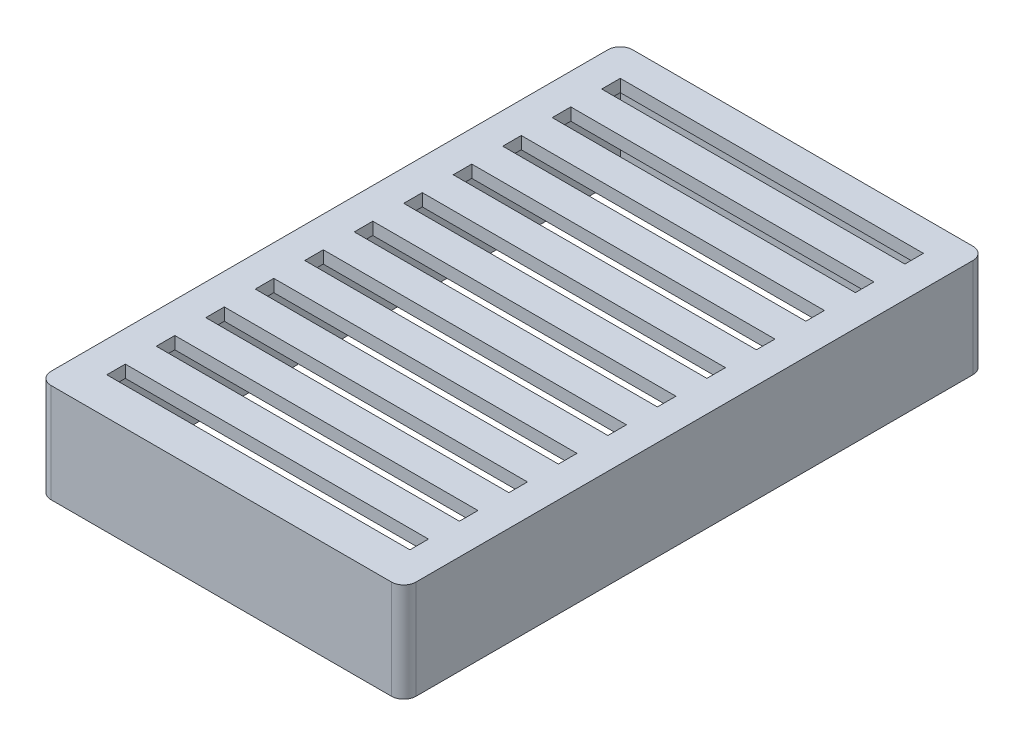
SolidWorks part; units mm, degrees
ref_plane "Front Plane" through (0, 0, 0) normal (0, 0, 1) x (1, 0, 0)
ref_plane "Top Plane" through (0, 0, 0) normal (0, 1, 0) x (1, 0, 0)
ref_plane "Right Plane" through (0, 0, 0) normal (1, 0, 0) x (0, 0, -1)
sketch "Sketch1" plane through (0, 15, 0) normal (0, 1, 0) x (1, 0, 0)
  line L27 (26.5, 24) -> (-26.5, 24)
  line L28 (-26.5, 24) -> (-26.5, -64)
  line L29 (-26.5, -64) -> (26.5, -64)
  line L30 (26.5, -64) -> (26.5, 24)
  line L31 (-27.5, -67) -> (27.5, -67)
  line L32 (-29.5, 25) -> (-29.5, -65)
  line L33 (27.5, 27) -> (-27.5, 27)
  line L34 (29.5, -65) -> (29.5, 25)
  line L35 (-27.5, -67) -> (27.5, -67)
  line L36 (-29.5, 25) -> (-29.5, -65)
  line L37 (27.5, 27) -> (-27.5, 27)
  line L38 (29.5, -65) -> (29.5, 25)
  line L39 (0, 24) -> (0, -64) construction
  line L41 (-11, 24) -> (-9, 24)
  line L44 (-11, -64) -> (-9, -64)
  line L49 (0, 21.1819) -> (0, 0) construction
  line L51 (-26.5, 22) -> (-26.5, 20)
  line L53 (0, 22) -> (0, 20)
  arc A24 (-26.5, 24) -> (-26.5, 24) centre (-26.5, 24) ccw
  arc A25 (-26.5, -64) -> (-26.5, -64) centre (-26.5, -64) ccw
  arc A26 (26.5, -64) -> (26.5, -64) centre (26.5, -64) ccw
  arc A27 (26.5, 24) -> (26.5, 24) centre (26.5, 24) ccw
  arc A28 (27.5, -67) -> (29.5, -65) centre (27.5, -65) ccw
  arc A29 (-29.5, -65) -> (-27.5, -67) centre (-27.5, -65) ccw
  arc A30 (-27.5, 27) -> (-29.5, 25) centre (-27.5, 25) ccw
  arc A31 (29.5, 25) -> (27.5, 27) centre (27.5, 25) ccw
  arc A32 (27.5, -67) -> (29.5, -65) centre (27.5, -65) ccw
  arc A33 (-29.5, -65) -> (-27.5, -67) centre (-27.5, -65) ccw
  arc A34 (-27.5, 27) -> (-29.5, 25) centre (-27.5, 25) ccw
  arc A35 (29.5, 25) -> (27.5, 27) centre (27.5, 25) ccw
  dimension "D1" = 1
  dimension "D2" = 3
extrude "Boss-Extrude1" add sketch "Sketch1" against normal offset from surface 1 and the other way blind 5 contours L38 A35 L37 A34 L36 A33 L35 A32 L30 L29 L28 L27
sketch "Sketch2" plane through (0, 20, 0) normal (0, 1, 0) x (1, 0, 0)
  line L18 (29.5, -65) -> (29.5, 25)
  line L19 (27.5, 27) -> (-27.5, 27)
  line L20 (-29.5, 25) -> (-29.5, -65)
  line L21 (-27.5, -67) -> (27.5, -67)
  line L22 (29.5, -65) -> (29.5, 25)
  line L23 (27.5, 27) -> (-27.5, 27)
  line L24 (-29.5, 25) -> (-29.5, -65)
  line L25 (-27.5, -67) -> (27.5, -67)
  arc A16 (29.5, 25) -> (27.5, 27) centre (27.5, 25) ccw
  arc A17 (-27.5, 27) -> (-29.5, 25) centre (-27.5, 25) ccw
  arc A18 (-29.5, -65) -> (-27.5, -67) centre (-27.5, -65) ccw
  arc A19 (27.5, -67) -> (29.5, -65) centre (27.5, -65) ccw
  arc A20 (29.5, 25) -> (27.5, 27) centre (27.5, 25) ccw
  arc A21 (-27.5, 27) -> (-29.5, 25) centre (-27.5, 25) ccw
  arc A22 (-29.5, -65) -> (-27.5, -67) centre (-27.5, -65) ccw
  arc A23 (27.5, -67) -> (29.5, -65) centre (27.5, -65) ccw
  dimension "D1" = 0
extrude "Boss-Extrude3" add sketch "Sketch2" along normal blind 2
sketch "Sketch7" plane through (0, 22, 0) normal (0, 1, 0) x (1, 0, 0)
  line L0 (0, 20.5) -> (0, -64) construction
  line L1 (-24.5, 19) -> (24.5, 19)
  line L2 (-24.5, 19) -> (-24.5, 22)
  line L3 (-24.5, 22) -> (24.5, 22)
  line L4 (24.5, 19) -> (24.5, 22)
  line L5 (-24.5, 19) -> (24.5, 22) construction
  line L6 (-24.5, 22) -> (24.5, 19) construction
  line L7 (0, 24) -> (0, -64) construction
  line L8 (26.5, 24) -> (-26.5, 24) construction
  line L9 (26.5, -64) -> (26.5, 24) construction
  point P0 (0, 20.5)
  point P8 (0, 0)
  point P9 (0, 0)
  dimension "D1" = 2
  dimension "D2" = 3
  dimension "D3" = 2
extrude "Cut-Extrude3" cut sketch "Sketch7" against normal through all
pattern_linear "LPattern1" count 11 spacing 8 along (0, 0, 1) of "Cut-Extrude3"
